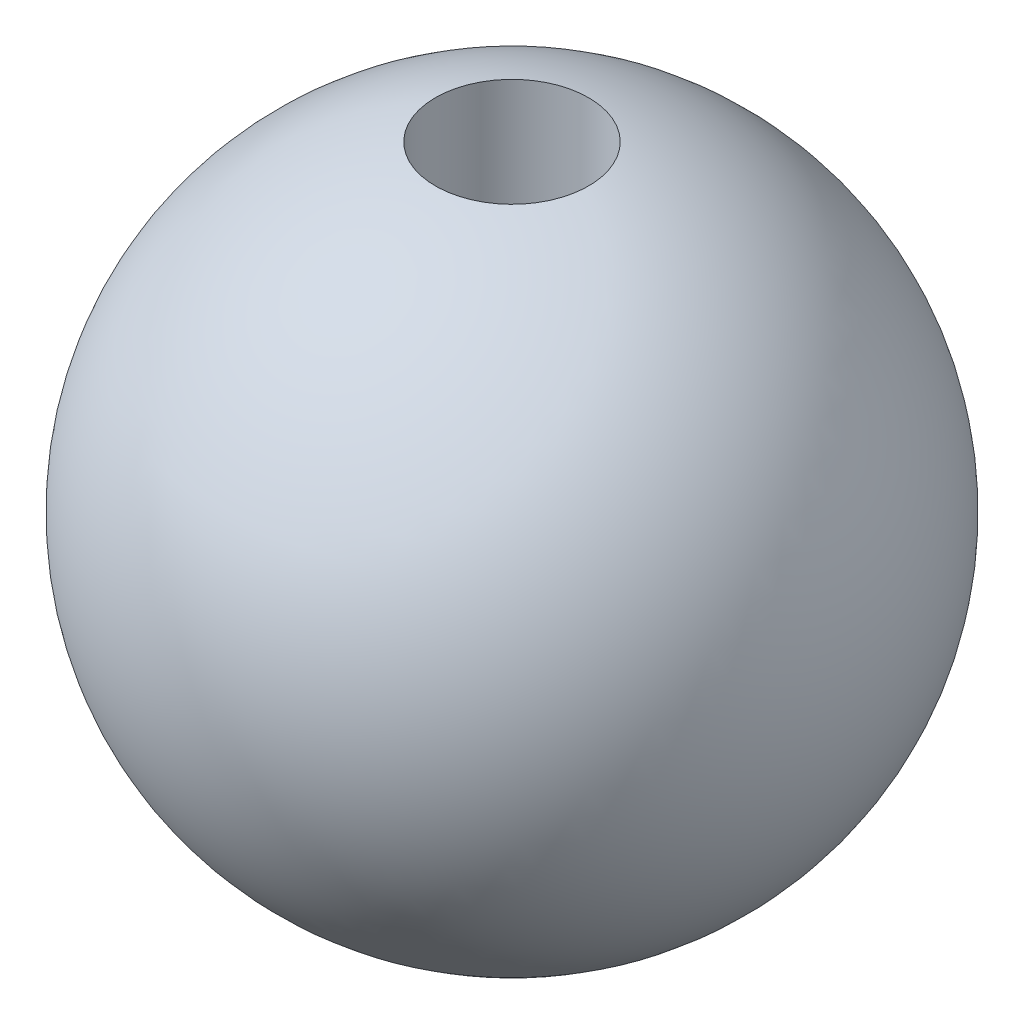
SolidWorks part; units mm, degrees
ref_plane "前视基准面" through (0, 0, 0) normal (0, 0, 1) x (1, 0, 0)
ref_plane "上视基准面" through (0, 0, 0) normal (0, 1, 0) x (1, 0, 0)
ref_plane "右视基准面" through (0, 0, 0) normal (1, 0, 0) x (0, 0, -1)
sketch "草图1" plane through (0, 0, 0) normal (0, 0, 1) x (1, 0, 0)
  line L0 (0, 0) -> (0, 371438.6167) construction
  line L1 (-190, 795.6281) -> (-190, 177.4824)
  line L2 (-190, -373.1696) -> (-190, -795.6281)
  arc A0 (-190, 177.4824) -> (-254.8462, -51.5112) centre (0, 0) ccw
  arc A1 (-254.8462, -51.5112) -> (-190, -373.1696) centre (0, -167.5) ccw
  arc A2 (-190, 795.6281) -> (-190, -795.6281) centre (0, 0) ccw
  point P12 (0, 0)
  point P13 (0, 0)
  dimension "D1" = 260
  dimension "D2" = 280
  dimension "D5" = 818
  dimension "D3" = 167.5
  dimension "D4" = 380
revolve "旋转1" add sketch "草图1" angle 360 about L0
